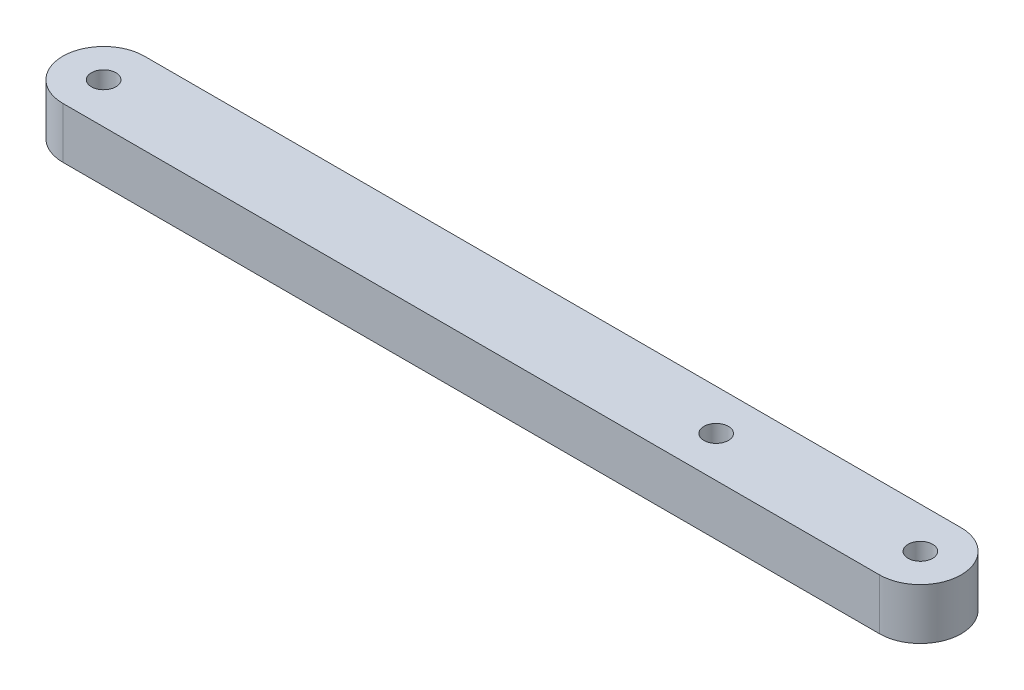
SolidWorks part; units mm, degrees
ref_plane "Front Plane" through (0, 0, 0) normal (0, 0, 1) x (1, 0, 0)
ref_plane "Top Plane" through (0, 0, 0) normal (0, 1, 0) x (1, 0, 0)
ref_plane "Right Plane" through (0, 0, 0) normal (1, 0, 0) x (0, 0, -1)
sketch "Sketch1" plane through (0, 0, 0) normal (0, 1, 0) x (1, 0, 0)
  line L0 (0, 0) -> (400, 0) construction
  line L1 (0, 20) -> (400, 20)
  line L2 (0, -20) -> (400, -20)
  arc A0 (0, 20) -> (0, -20) centre (0, 0) ccw
  arc A1 (400, -20) -> (400, 20) centre (400, 0) ccw
  circle A2 centre (300, 0) radius 6
  circle A3 centre (400, 0) radius 6
  circle A4 centre (0, 0) radius 6
  point P3 (200, 0)
  dimension "D4" = 12
  dimension "D5" = 12
  dimension "D6" = 12
  dimension "D1" = 400
  dimension "D2" = 300
  dimension "D3" = 40
extrude "Boss-Extrude1" add sketch "Sketch1" along normal blind 25
